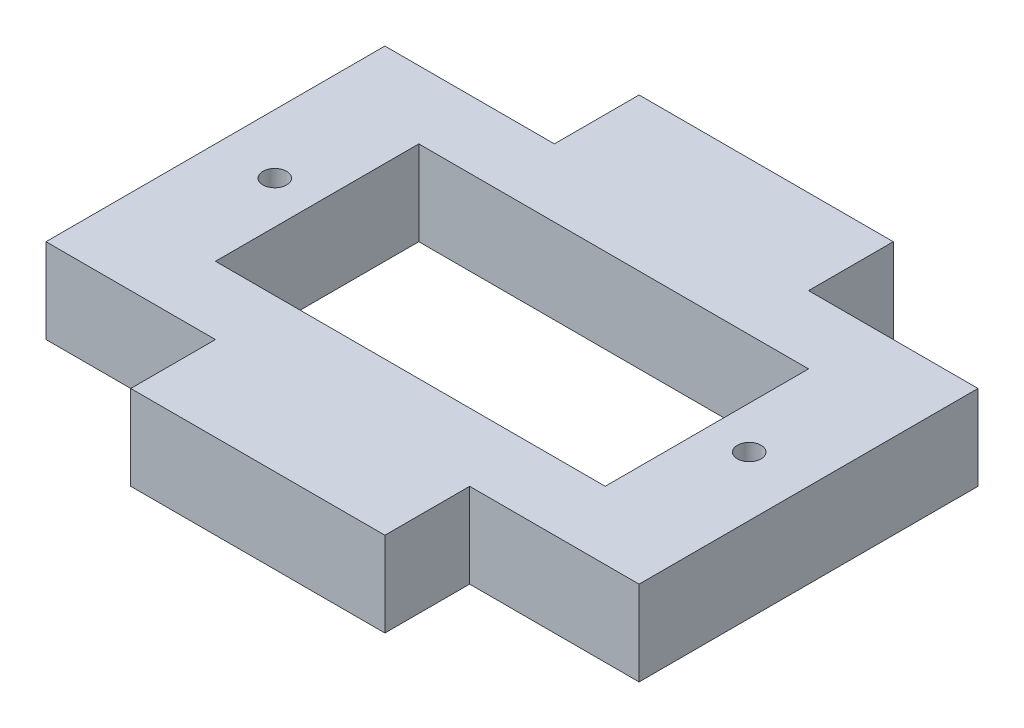
SolidWorks part; units mm, degrees
ref_plane "Front Plane" through (0, 0, 0) normal (0, 0, 1) x (1, 0, 0)
ref_plane "Top Plane" through (0, 0, 0) normal (0, 1, 0) x (1, 0, 0)
ref_plane "Right Plane" through (0, 0, 0) normal (1, 0, 0) x (0, 0, -1)
sketch "Sketch1" plane through (0, 0, 0) normal (0, 1, 0) x (1, 0, 0)
  line L0 (7.5, 10) -> (17.5, 10)
  line L1 (-17.5, -10) -> (-7.5, -10)
  line L2 (-17.5, -10) -> (-17.5, 10)
  line L3 (-17.5, 10) -> (-7.5, 10)
  line L4 (17.5, -10) -> (17.5, 10)
  line L7 (-11.5, -6) -> (11.5, -6)
  line L8 (-11.5, -6) -> (-11.5, 6)
  line L9 (-11.5, 6) -> (11.5, 6)
  line L10 (11.5, -6) -> (11.5, 6)
  line L14 (-7.5, 10) -> (-7.5, 15)
  line L15 (-7.5, 15) -> (7.5, 15)
  line L16 (7.5, 10) -> (7.5, 15)
  line L18 (-7.5, -10) -> (-7.5, -15)
  line L19 (-7.5, -15) -> (7.5, -15)
  line L20 (7.5, -10) -> (7.5, -15)
  line L21 (7.5, -10) -> (17.5, -10)
  circle A0 centre (-14, 0) radius 0.7
  circle A1 centre (14, 0) radius 0.7
  point P0 (0, 0)
  point P10 (0, 0)
  dimension "D6" = 1.4
  dimension "D7" = 1.4
  dimension "D1" = 20
  dimension "D2" = 28
  dimension "D3" = 14
  dimension "D4" = 12
  dimension "D5" = 23
  dimension "D8" = 35
  dimension "D9" = 15
  dimension "D10" = 10
  dimension "D11" = 5
  dimension "D12" = 5
extrude "Boss-Extrude1" add sketch "Sketch1" along normal blind 5
